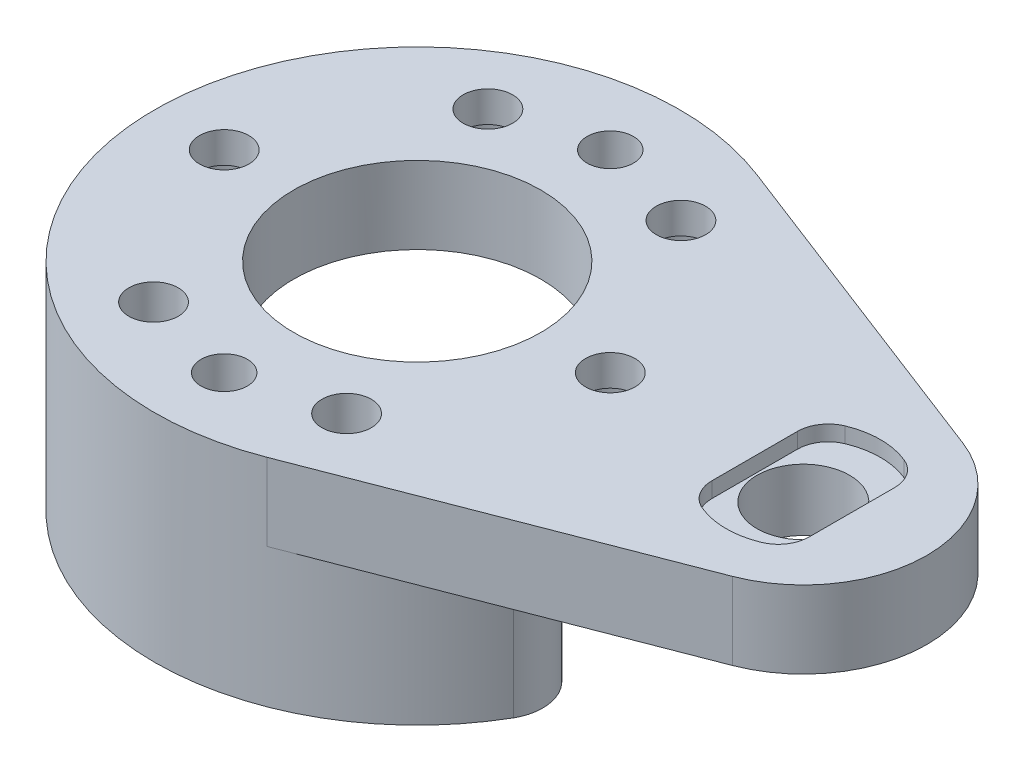
SolidWorks part; units mm, degrees
ref_plane "Спереди" through (0, 0, 0) normal (0, 0, 1) x (1, 0, 0)
ref_plane "Сверху" through (0, 0, 0) normal (0, 1, 0) x (1, 0, 0)
ref_plane "Справа" through (0, 0, 0) normal (1, 0, 0) x (0, 0, -1)
ref_plane "Плоскость4" through (0, 0, 0) normal (0, -1, 0) x (1, 0, 0)
sketch "Эскиз1" plane through (0, 0, 0) normal (0, -1, 0) x (1, 0, 0)
  line L0 (6.12, -15.8602) -> (27.88, -7.4636)
  line L1 (27.88, 7.4636) -> (6.12, 15.8602)
  arc A0 (6.12, 15.8602) -> (6.12, -15.8602) centre (0, 0) ccw
  arc A1 (27.88, -7.4636) -> (27.88, 7.4636) centre (25, 0) ccw
extrude "Бобышка-Вытянуть1" add sketch "Эскиз1" against normal blind 5
sketch "Эскиз2" plane through (0, 5, 0) normal (0, 1, 0) x (-1, 0, 0)
  line L0 (12.1244, 4) -> (-12.1244, 4)
  arc A0 (-12.1244, 4) -> (-14.7224, 8.5) centre (-12.1244, 7) cw
  arc A1 (-14.7224, 8.5) -> (14.7224, 8.5) centre (0, 0) cw
  arc A2 (14.7224, 8.5) -> (12.1244, 4) centre (12.1244, 7) cw
extrude "Бобышка-Вытянуть2" add sketch "Эскиз2" along normal blind 9
sketch "Эскиз3" plane through (0, 0, 0) normal (0, -1, 0) x (1, 0, 0)
  line L0 (21.85, 3.883) -> (21.85, -3.883)
  line L1 (28.15, -3.883) -> (28.15, 3.883)
  arc A0 (28.15, 3.883) -> (21.85, 3.883) centre (25, 0) ccw
  arc A1 (21.85, -3.883) -> (28.15, -3.883) centre (25, 0) ccw
extrude "Вырез-Вытянуть1" cut sketch "Эскиз3" against normal blind 1
hole_wizard "Диаметр отверстия Ø3.0 (3)1" positions "Эскиз5" profile "Эскиз4" hole size "Ø3.0" standard "Ansi Metric"
sketch "Эскиз5" plane through (0, 0, 0) normal (0, -1, 0) x (-1, 0, 0)
  point P0 (0, 12.5)
sketch "Эскиз4" plane through (0, 0, -12.5) normal (1, 0, 0) x (0, 0, -1)
  line L0 (0, 0) -> (0, 4.4013)
  line L1 (0, 4.4013) -> (1.5, 3.5)
  line L2 (1.5, 3.5) -> (1.5, 0)
  line L5 (1.5, 0) -> (0, 0)
  line L10 (0, 4.4013) -> (-1.5, 3.5) construction
  line L11 (0, -6.35) -> (0, 107.95) construction
  dimension "Диаметр отверстия" = 3
  dimension "Глубина отверстия" = 3.5
  dimension "Угол заточки сверла" = 118
hole_wizard "Диаметр отверстия Ø3.0 (3)2" positions "Эскиз7" profile "Эскиз6" hole size "Ø3.0" standard "Ansi Metric"
sketch "Эскиз7" plane through (0, 0, 0) normal (0, -1, 0) x (-1, 0, 0)
  point P0 (0, -12.5)
sketch "Эскиз6" plane through (0, 0, 12.5) normal (1, 0, 0) x (0, 0, -1)
  line L0 (0, 0) -> (0, 4.4013)
  line L1 (0, 4.4013) -> (1.5, 3.5)
  line L2 (1.5, 3.5) -> (1.5, 0)
  line L5 (1.5, 0) -> (0, 0)
  line L10 (0, 4.4013) -> (-1.5, 3.5) construction
  line L11 (0, -6.35) -> (0, 107.95) construction
  dimension "Диаметр отверстия" = 3
  dimension "Глубина отверстия" = 3.5
  dimension "Угол заточки сверла" = 118
hole_wizard "Цековка для винта с заклепочной головкой M31" positions "Эскиз9" profile "Эскиз8" counterbore size "M3" standard "Ansi Metric"
sketch "Эскиз9" plane through (0, 5, 0) normal (0, 1, 0) x (1, 0, 0)
  point P0 (12.5, 0)
  point P1 (6.25, 10.8253)
  point P2 (-6.25, 10.8253)
  point P3 (-12.5, 0)
sketch "Эскиз8" plane through (12.5, 5, 0) normal (1, 0, 0) x (0, 0, 1)
  line L0 (0, 0) -> (0, 5)
  line L1 (0, 5) -> (1.6, 5)
  line L3 (1.6, 5) -> (1.6, 3)
  line L4 (1.6, 3) -> (3.025, 3)
  line L5 (3.025, 3) -> (3.025, 0)
  line L7 (3.025, 0) -> (0, 0)
  line L11 (0, -6.35) -> (0, 107.95) construction
  dimension "Диаметр сквозного отверстия" = 3.2
  dimension "Глубина сквозного отверстия" = 5
  dimension "Диаметр цековки" = 6.05
  dimension "Глубина цековки" = 3
hole_wizard "Диаметр отверстия Ø16.0 (16)1" positions "Эскиз11" profile "Эскиз10" hole size "Ø16.0" standard "Ansi Metric"
sketch "Эскиз11" plane through (0, 0, 0) normal (0, -1, 0) x (-1, 0, 0)
  point P0 (0, 0)
sketch "Эскиз10" plane through (0, 0, 0) normal (1, 0, 0) x (0, 0, -1)
  line L0 (0, 0) -> (0, 14)
  line L1 (0, 14) -> (8, 14)
  line L2 (8, 14) -> (8, 0)
  line L5 (8, 0) -> (0, 0)
  line L11 (0, -6.35) -> (0, 107.95) construction
  dimension "Диаметр сквозного отверстия" = 16
  dimension "Глубина сквозного отверстия" = 14
hole_wizard "Диаметр отверстия Ø3.2 (3.2)1" positions "Эскиз13" profile "Эскиз12" hole size "Ø3.2" standard "Ansi Metric"
sketch "Эскиз13" plane through (0, 0, 0) normal (0, -1, 0) x (-1, 0, 0)
  point P0 (6.25, -10.8253)
  point P1 (-6.25, -10.8253)
sketch "Эскиз12" plane through (-6.25, 0, 10.8253) normal (1, 0, 0) x (0, 0, -1)
  line L0 (0, 0) -> (0, 14)
  line L1 (0, 14) -> (1.6, 14)
  line L2 (1.6, 14) -> (1.6, 0)
  line L5 (1.6, 0) -> (0, 0)
  line L11 (0, -6.35) -> (0, 107.95) construction
  dimension "Диаметр сквозного отверстия" = 3.2
  dimension "Глубина сквозного отверстия" = 14
hole_wizard "Диаметр отверстия Ø6.0 (6)1" positions "Эскиз15" profile "Эскиз14" hole size "Ø6.0" standard "Ansi Metric"
sketch "Эскиз15" plane through (0, 1, 0) normal (0, -1, 0) x (-1, 0, 0)
  point P0 (-25, 0)
sketch "Эскиз14" plane through (25, 1, 0) normal (1, 0, 0) x (0, 0, -1)
  line L0 (0, 0) -> (0, 13)
  line L1 (0, 13) -> (3, 13)
  line L2 (3, 13) -> (3, 0)
  line L5 (3, 0) -> (0, 0)
  line L11 (0, -6.35) -> (0, 107.95) construction
  dimension "Диаметр сквозного отверстия" = 6
  dimension "Глубина сквозного отверстия" = 13
fillet "Скругление1" radius 2 4 edges at (28.15, 0.5, -3.883) (28.15, 0.5, 3.883) (21.85, 0.5, 3.883) (21.85, 0.5, -3.883)
fillet "Скругление2" radius 3 2 edges at (6.9282, 9.5, 4) (-6.9282, 9.5, 4)
mirror "Зеркальное отражение1" about plane through (0, 0, 0) normal (0, -1, 0) of bodies 111
delete or keep bodies "Тело-Удалить/Сохранить 1" type delete bodies bodies 111
